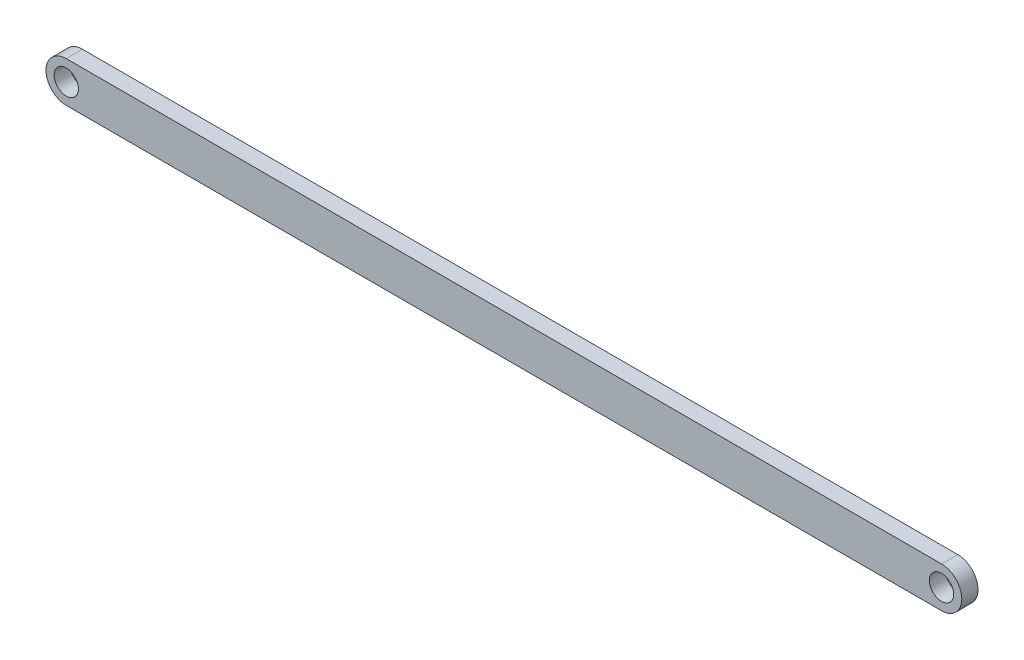
SolidWorks part; units mm, degrees
ref_plane "Plano frontal" through (0, 0, 0) normal (0, 0, 1) x (1, 0, 0)
ref_plane "Plano superior" through (0, 0, 0) normal (0, 1, 0) x (1, 0, 0)
ref_plane "Plano direito" through (0, 0, 0) normal (1, 0, 0) x (0, 0, -1)
sketch "Esboço1" plane through (0, 0, 0) normal (0, 0, 1) x (1, 0, 0)
  line L0 (0, 0) -> (108, 0) construction
  line L1 (0, 2.5) -> (108, 2.5)
  line L2 (0, -2.5) -> (108, -2.5)
  circle A0 centre (0, 0) radius 1.5
  circle A1 centre (108, 0) radius 1.5
  arc A2 (0, 2.5) -> (0, -2.5) centre (0, 0) ccw
  arc A3 (108, -2.5) -> (108, 2.5) centre (108, 0) ccw
  point P5 (54, 0)
  dimension "D1" = 3
  dimension "D2" = 108
  dimension "D3" = 5
extrude "Ressalto-extrusão1" add sketch "Esboço1" along normal blind 2
